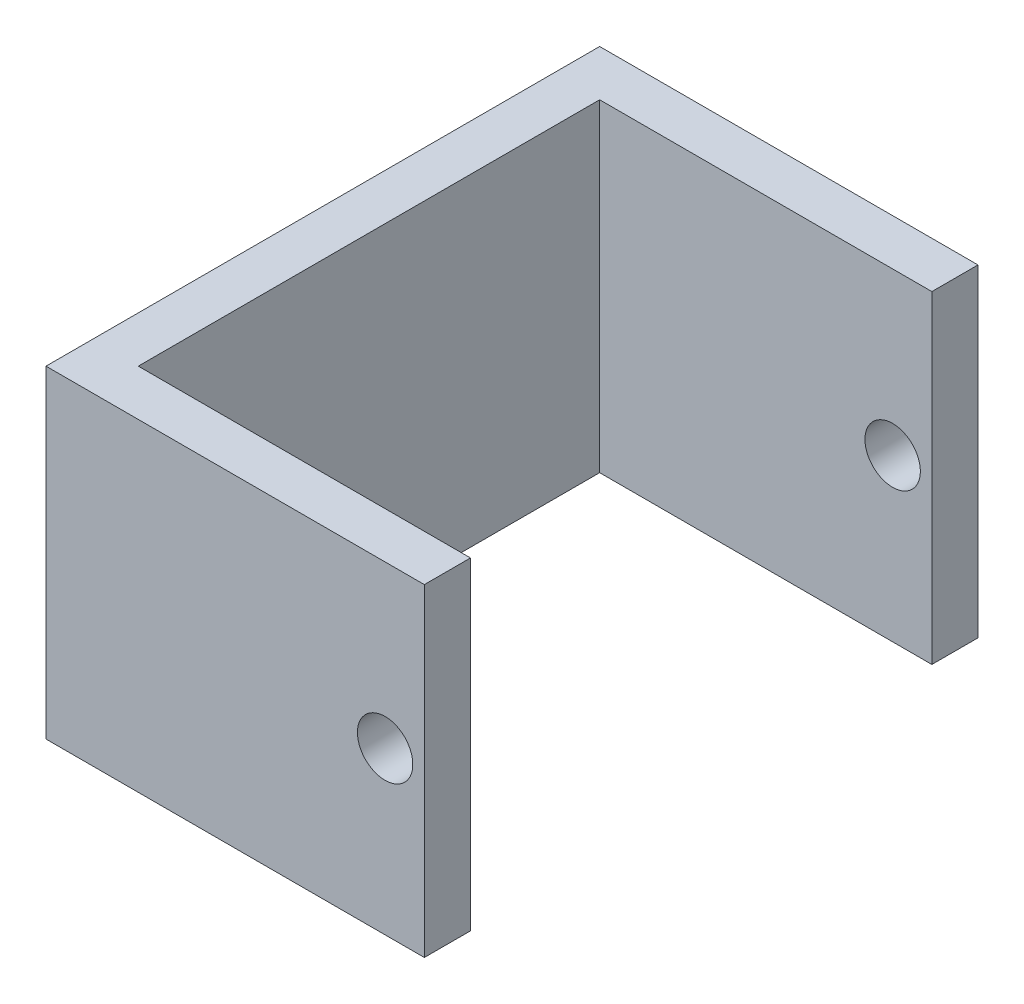
SolidWorks part; units mm, degrees
ref_plane "Front Plane" through (0, 0, 0) normal (1, 0, 0) x (0, 1, 0)
ref_plane "Top Plane" through (0, 0, 0) normal (0, 0, 1) x (0, 1, 0)
ref_plane "Right Plane" through (0, 0, 0) normal (0, 1, 0) x (-1, 0, 0)
sketch "Sketch1" plane through (0, 0, 0) normal (1, 0, 0) x (0, 1, 0)
  line L1 (-35, -60) -> (35, -60)
  line L2 (-35, -60) -> (-35, 60)
  line L3 (-35, 60) -> (35, 60)
  line L4 (35, -60) -> (35, 60)
  line L5 (-35, -60) -> (35, 60) construction
  line L6 (-35, 60) -> (35, -60) construction
  point P0 (0, 0)
  dimension "D1" = 70
  dimension "D2" = 120
extrude "Boss-Extrude3" add sketch "Sketch1" along normal blind 10
sketch "Sketch3" plane through (10, 0, 0) normal (1, 0, 0) x (0, 1, 0)
  line L0 (35, -60) -> (35, 60) construction
  line L1 (-35, 60) -> (35, 60)
  line L2 (-35, 60) -> (-35, 50)
  line L3 (-35, 50) -> (35, 50)
  line L4 (35, 60) -> (35, 50)
  line L6 (35, -60) -> (35, -50)
  line L7 (-35, -60) -> (35, -60)
  line L8 (-35, -60) -> (-35, -50)
  line L9 (-35, -50) -> (35, -50)
  dimension "D1" = 10
extrude "Boss-Extrude4" add sketch "Sketch3" along normal blind 72
sketch "Sketch4" plane through (0, 0, -60) normal (0, 0, -1) x (1, 0, 0)
  circle A0 centre (73.5, 0) radius 6
  dimension "D2" = 12
extrude "Cut-Extrude1" cut sketch "Sketch4" against normal through all both and the other way through all
